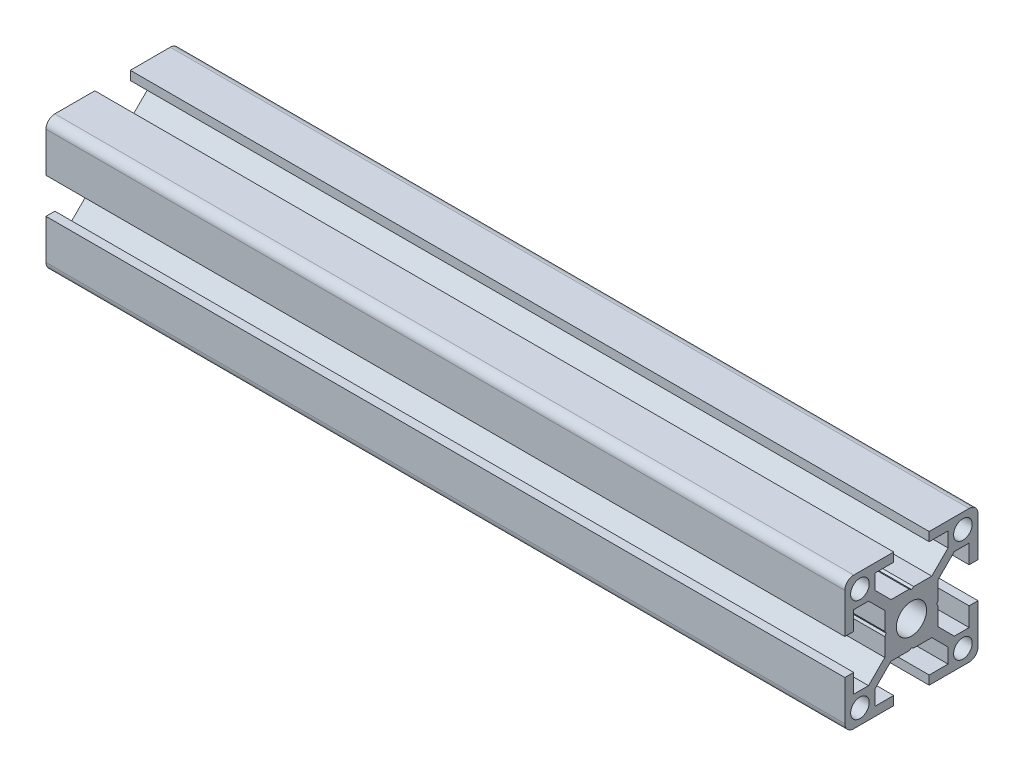
SolidWorks part; units mm, degrees
ref_plane "Front Plane" through (0, 0, 0) normal (0, 0, 1) x (1, 0, 0)
ref_plane "Top Plane" through (0, 0, 0) normal (0, 1, 0) x (1, 0, 0)
ref_plane "Right Plane" through (0, 0, 0) normal (1, 0, 0) x (0, 0, -1)
ref_plane "Plane1" through (0, 0, 0) normal (-1, 0, 0) x (0, -1, 0)
sketch "Sketch1" plane through (0, 0, 0) normal (-1, 0, 0) x (0, -1, 0)
  line L0 (13, -4) -> (13, -8.25)
  line L1 (13, -8.25) -> (9.6642, -8.25)
  line L2 (9.6642, -8.25) -> (6, -4.5858)
  line L3 (6, -4.5858) -> (6, -0.5196)
  line L4 (6, -0.5196) -> (5.7, 0)
  line L5 (5.7, 0) -> (6, 0.5196)
  line L6 (6, 0.5196) -> (6, 4.5858)
  line L7 (6, 4.5858) -> (9.6642, 8.25)
  line L8 (9.6642, 8.25) -> (13, 8.25)
  line L9 (13, 8.25) -> (13, 4)
  line L10 (13, 4) -> (15, 4)
  line L11 (15, 4) -> (15, 13)
  line L12 (13, 15) -> (4, 15)
  line L13 (4, 15) -> (4, 13)
  line L14 (4, 13) -> (8.25, 13)
  line L15 (8.25, 13) -> (8.25, 9.6642)
  line L16 (8.25, 9.6642) -> (4.5858, 6)
  line L17 (4.5858, 6) -> (0.5196, 6)
  line L18 (0.5196, 6) -> (0, 5.7)
  line L19 (0, 5.7) -> (-0.5196, 6)
  line L20 (-0.5196, 6) -> (-4.5858, 6)
  line L21 (-4.5858, 6) -> (-8.25, 9.6642)
  line L22 (-8.25, 9.6642) -> (-8.25, 13)
  line L23 (-8.25, 13) -> (-4, 13)
  line L24 (-4, 13) -> (-4, 15)
  line L25 (-4, 15) -> (-13, 15)
  line L26 (-15, 13) -> (-15, 4)
  line L27 (-15, 4) -> (-13, 4)
  line L28 (-13, 4) -> (-13, 8.25)
  line L29 (-13, 8.25) -> (-9.6642, 8.25)
  line L30 (-9.6642, 8.25) -> (-6, 4.5858)
  line L31 (-6, 4.5858) -> (-6, 0.5196)
  line L32 (-6, 0.5196) -> (-5.7, 0)
  line L33 (-5.7, 0) -> (-6, -0.5196)
  line L34 (-6, -0.5196) -> (-6, -4.5858)
  line L35 (-6, -4.5858) -> (-9.6642, -8.25)
  line L36 (-9.6642, -8.25) -> (-13, -8.25)
  line L37 (-13, -8.25) -> (-13, -4)
  line L38 (-13, -4) -> (-15, -4)
  line L39 (-15, -4) -> (-15, -13)
  line L40 (-13, -15) -> (-4, -15)
  line L41 (-4, -15) -> (-4, -13)
  line L42 (-4, -13) -> (-8.25, -13)
  line L43 (-8.25, -13) -> (-8.25, -9.6642)
  line L44 (-8.25, -9.6642) -> (-4.5858, -6)
  line L45 (-4.5858, -6) -> (-0.5196, -6)
  line L46 (-0.5196, -6) -> (0, -5.7)
  line L47 (0, -5.7) -> (0.5196, -6)
  line L48 (0.5196, -6) -> (4.5858, -6)
  line L49 (4.5858, -6) -> (8.25, -9.6642)
  line L50 (8.25, -9.6642) -> (8.25, -13)
  line L51 (8.25, -13) -> (4, -13)
  line L52 (4, -13) -> (4, -15)
  line L53 (4, -15) -> (13, -15)
  line L54 (15, -13) -> (15, -4)
  line L55 (15, -4) -> (13, -4)
  arc A0 (15, 13) -> (13, 15) centre (13, 13) ccw
  arc A1 (-13, 15) -> (-15, 13) centre (-13, 13) ccw
  arc A2 (-15, -13) -> (-13, -15) centre (-13, -13) ccw
  arc A3 (13, -15) -> (15, -13) centre (13, -13) ccw
  circle A4 centre (0, 0) radius 3.4
  circle A5 centre (11.6, -11.6) radius 2.1
  circle A6 centre (11.6, 11.6) radius 2.1
  circle A7 centre (-11.6, 11.6) radius 2.1
  circle A8 centre (-11.6, -11.6) radius 2.1
extrude "Boss-Extrude1" add sketch "Sketch1" against normal blind 180
